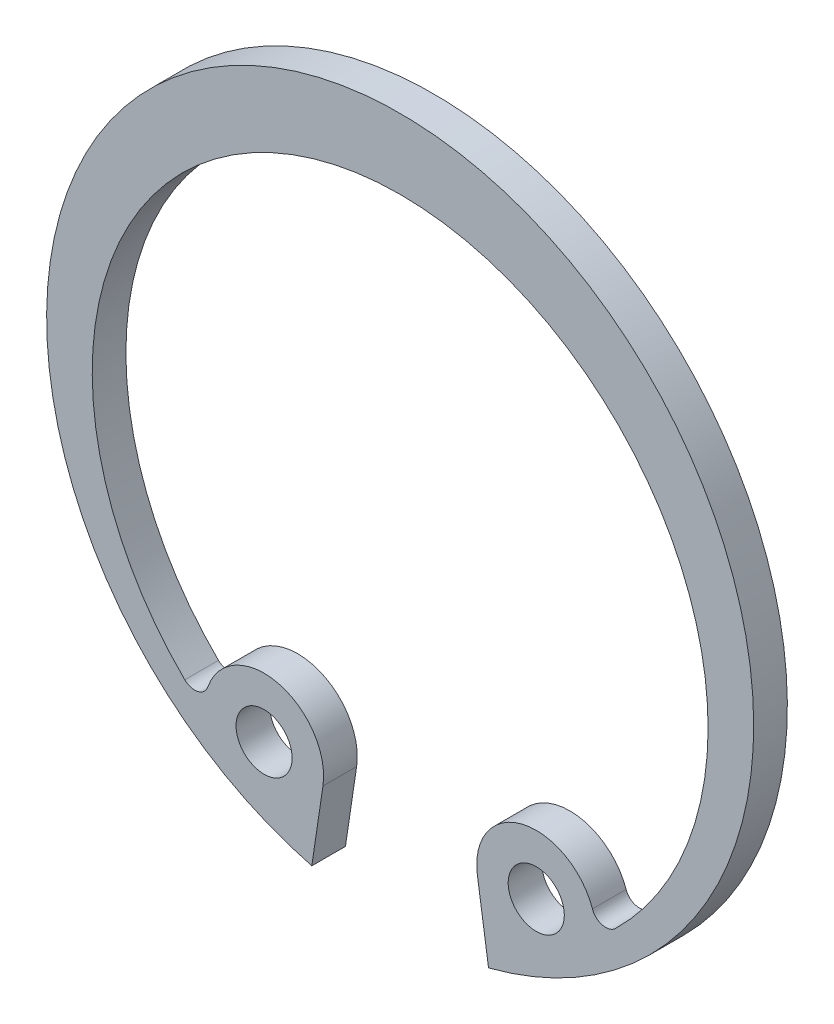
SolidWorks part; units mm, degrees
ref_plane "Front Plane" through (0, 0, 0) normal (0, 0, 1) x (1, 0, 0)
ref_plane "Top Plane" through (0, 0, 0) normal (0, 1, 0) x (1, 0, 0)
ref_plane "Right Plane" through (0, 0, 0) normal (1, 0, 0) x (0, 0, -1)
sketch "Sketch1" plane through (0, 0, 0) normal (0, 0, 1) x (1, 0, 0)
  line L0 (0, 0) -> (0, 12.6) construction
  line L1 (-2.7521, -9.5374) -> (-3.15, -12.1999)
  line L2 (2.7521, -9.5374) -> (3.15, -12.1999)
  line L3 (3.8628, -7.3463) -> (5.864, -11.1523) construction
  arc A0 (3.15, -12.1999) -> (-3.15, -12.1999) centre (0, 0) ccw
  arc A1 (-7.6753, -8.7198) -> (-6.8534, -8.5267) centre (-7.3256, -8.3624) ccw
  circle A2 centre (-4.85, -9.2238) radius 1
  circle A3 centre (4.85, -9.2238) radius 1
  circle A4 centre (0, 0) radius 7.5 construction
  arc A6 (-2.7521, -9.5374) -> (-6.8534, -8.5267) centre (-4.85, -9.2238) ccw
  arc A7 (6.8534, -8.5267) -> (2.7521, -9.5374) centre (4.85, -9.2238) ccw
  arc A8 (7.6753, -8.7198) -> (-7.6753, -8.7198) centre (0, -0.875) ccw
  arc A9 (7.6753, -8.7198) -> (6.8534, -8.5267) centre (7.3256, -8.3624) cw
  point P13 (0, 10.1)
  dimension "D1" = 0.5
  dimension "RIC_D2_s" = 25.2
  dimension "D2" = 17
  dimension "RIC_D4_s" = 21.95
  dimension "RIC_D0_s" = 2
  dimension "RIC_D5_s" = 15
  dimension "RIC_B_s" = 2.5
  dimension "RIC_MSM_2" = 9.7
  dimension "RIC_MSM_1" = 6.3
  dimension "RIC_A_s" = 4.3
extrude "Boss-Extrude1" add sketch "Sketch1" along normal blind 1.2
equation "\"RIC_D4_s@Sketch1\"=\"RIC_D2_s@Sketch1\"-1.3*\"RIC_B_s@Sketch1\""
